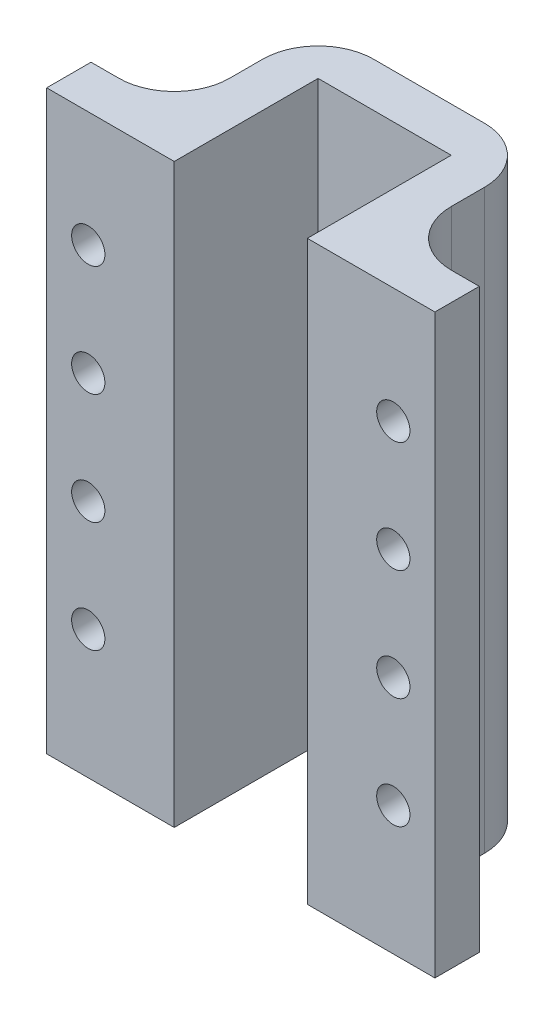
SolidWorks part; units mm, degrees
ref_plane "Спереди" through (0, 0, 0) normal (0, 0, 1) x (1, 0, 0)
ref_plane "Сверху" through (0, 0, 0) normal (0, 1, 0) x (1, 0, 0)
ref_plane "Справа" through (0, 0, 0) normal (1, 0, 0) x (0, 0, -1)
sketch "Эскиз1" plane through (0, 0, 0) normal (0, 1, 0) x (1, 0, 0)
  line L0 (-17.5, -8.4853) -> (-6, -8.4853)
  line L2 (-6, -8.4853) -> (-6, 4.5147)
  line L3 (-6, 4.4853) -> (6, 4.4853)
  line L4 (6, -8.4853) -> (6, 4.4853)
  line L5 (6, -8.4853) -> (17.5, -8.4853)
  line L6 (17.5, -8.4853) -> (17.5, -4.4853)
  line L7 (17.5, -4.4853) -> (10, -4.4853)
  line L8 (10, -4.4853) -> (10, 8.4853)
  line L9 (10, 8.4853) -> (-10, 8.4853)
  line L10 (-10, 8.4853) -> (-10, -4.4853)
  line L11 (-10, -4.4853) -> (-17.5, -4.4853)
  line L12 (-17.5, -4.4853) -> (-17.5, -8.4853)
  dimension "D1" = 11.5
  dimension "D2" = 4
  dimension "D3" = 12.9706
  dimension "D4" = 4
  dimension "D5" = 4
  dimension "D6" = 12.9706
extrude "Бобышка-Вытянуть1" add sketch "Эскиз1" along normal blind 52
fillet "Скругление1" radius 5 4 edges at (-10, 26, -8.4853) (10, 26, -8.4853) (-10, 26, 4.4853) (10, 26, 4.4853)
ref_plane "Плоскость1" through (0, 0, 18.4853) normal (0, 0, 1) x (1, 0, 0)
ref_plane "Плоскость2" through (0, 0, 4.4853) normal (0, 0, -1) x (-1, 0, 0)
sketch "Эскиз2" plane through (0, 0, 4.4853) normal (0, 0, -1) x (-1, 0, 0)
  line L0 (13.75, 52) -> (13.75, 0) construction
  line L10 (-13.75, 52) -> (-13.75, 0) construction
  circle A8 centre (13.75, 41.6) radius 1.5
  circle A9 centre (13.75, 31.6) radius 1.5
  circle A10 centre (13.75, 21.6) radius 1.5
  circle A11 centre (13.75, 11.6) radius 1.5
  circle A12 centre (-13.75, 41.6) radius 1.5
  circle A13 centre (-13.75, 31.6) radius 1.5
  circle A14 centre (-13.75, 21.6) radius 1.5
  circle A15 centre (-13.75, 11.6) radius 1.5
  dimension "D4" = 4
  dimension "D3" = 4
extrude "Вырез-Вытянуть1" cut sketch "Эскиз2" against normal blind 10 and the other way blind 10
sketch "Эскиз3" plane through (0, 0, 4.4853) normal (0, 0, -1) x (-1, 0, 0)
  line L0 (0, 52) -> (0, 0) construction
  line L1 (13.75, 38.4246) -> (16.5, 40.0123)
  line L2 (16.5, 40.0123) -> (16.5, 43.1877)
  line L3 (16.5, 43.1877) -> (13.75, 44.7754)
  line L4 (13.75, 44.7754) -> (11, 43.1877)
  line L5 (11, 43.1877) -> (11, 40.0123)
  line L6 (11, 40.0123) -> (13.75, 38.4246)
  line L7 (-5, 52) -> (5, 52) construction
  line L8 (-11, 40.0123) -> (-13.75, 38.4246)
  line L9 (-11, 43.1877) -> (-11, 40.0123)
  line L10 (-13.75, 44.7754) -> (-11, 43.1877)
  line L11 (-16.5, 43.1877) -> (-13.75, 44.7754)
  line L12 (-16.5, 40.0123) -> (-16.5, 43.1877)
  line L13 (-13.75, 38.4246) -> (-16.5, 40.0123)
  line L14 (13.75, 28.4246) -> (16.5, 30.0123)
  line L15 (16.5, 30.0123) -> (16.5, 33.1877)
  line L16 (16.5, 33.1877) -> (13.75, 34.7754)
  line L17 (13.75, 34.7754) -> (11, 33.1877)
  line L18 (11, 33.1877) -> (11, 30.0123)
  line L19 (11, 30.0123) -> (13.75, 28.4246)
  line L20 (-11, 30.0123) -> (-13.75, 28.4246)
  line L21 (-13.75, 28.4246) -> (-16.5, 30.0123)
  line L22 (-16.5, 30.0123) -> (-16.5, 33.1877)
  line L23 (-16.5, 33.1877) -> (-13.75, 34.7754)
  line L24 (-13.75, 34.7754) -> (-11, 33.1877)
  line L25 (-11, 33.1877) -> (-11, 30.0123)
  line L26 (13.75, 18.4246) -> (16.5, 20.0123)
  line L27 (16.5, 20.0123) -> (16.5, 23.1877)
  line L28 (16.5, 23.1877) -> (13.75, 24.7754)
  line L29 (13.75, 24.7754) -> (11, 23.1877)
  line L30 (11, 23.1877) -> (11, 20.0123)
  line L31 (11, 20.0123) -> (13.75, 18.4246)
  line L32 (-11, 20.0123) -> (-13.75, 18.4246)
  line L33 (-13.75, 18.4246) -> (-16.5, 20.0123)
  line L34 (-16.5, 20.0123) -> (-16.5, 23.1877)
  line L35 (-16.5, 23.1877) -> (-13.75, 24.7754)
  line L36 (-13.75, 24.7754) -> (-11, 23.1877)
  line L37 (-11, 23.1877) -> (-11, 20.0123)
  line L38 (13.75, 8.4246) -> (16.5, 10.0123)
  line L39 (16.5, 10.0123) -> (16.5, 13.1877)
  line L40 (16.5, 13.1877) -> (13.75, 14.7754)
  line L41 (13.75, 14.7754) -> (11, 13.1877)
  line L42 (11, 13.1877) -> (11, 10.0123)
  line L43 (11, 10.0123) -> (13.75, 8.4246)
  line L44 (-11, 10.0123) -> (-13.75, 8.4246)
  line L45 (-13.75, 8.4246) -> (-16.5, 10.0123)
  line L46 (-16.5, 10.0123) -> (-16.5, 13.1877)
  line L47 (-16.5, 13.1877) -> (-13.75, 14.7754)
  line L48 (-13.75, 14.7754) -> (-11, 13.1877)
  line L49 (-11, 13.1877) -> (-11, 10.0123)
  circle A0 centre (13.75, 41.6) radius 2.75 construction
  dimension "D1" = 5.5
extrude "Вырез-Вытянуть2" cut sketch "Эскиз3" against normal blind 1.5 and the other way blind 10
